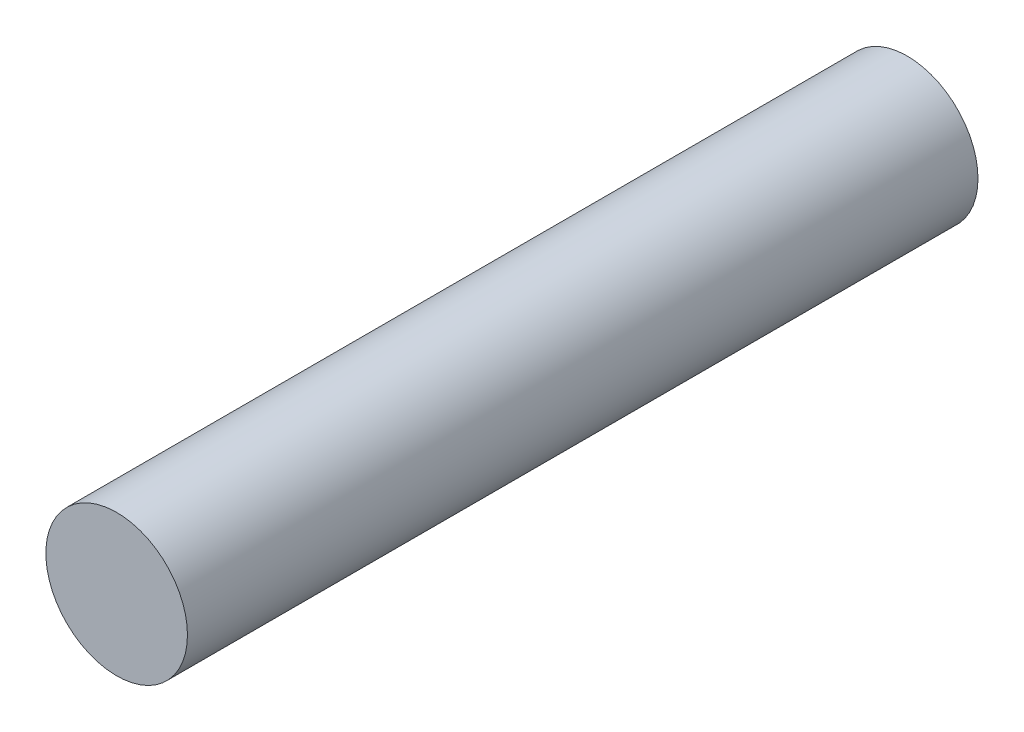
SolidWorks part; units mm, degrees
ref_plane "Front Plane" through (0, 0, 0) normal (0, 0, 1) x (1, 0, 0)
ref_plane "Top Plane" through (0, 0, 0) normal (0, 1, 0) x (1, 0, 0)
ref_plane "Right Plane" through (0, 0, 0) normal (1, 0, 0) x (0, 0, -1)
sketch "Sketch1" plane through (0, 0, 0) normal (0, 0, 1) x (1, 0, 0)
  circle A0 centre (0, 0) radius 6
  dimension "D1" = 12
extrude "Boss-Extrude1" add sketch "Sketch1" along normal blind 67
